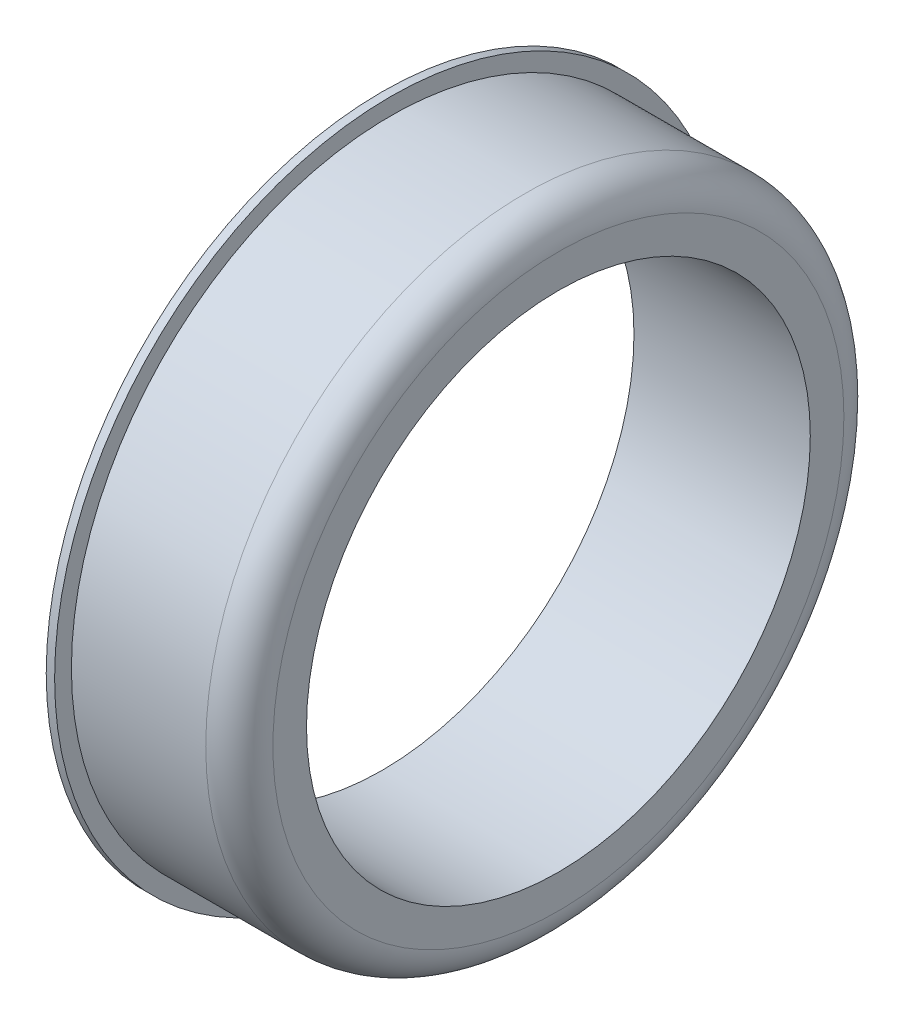
SolidWorks part; units mm, degrees
ref_plane "Front Plane" through (0, 0, 0) normal (0, 0, 1) x (1, 0, 0)
ref_plane "Top Plane" through (0, 0, 0) normal (0, 1, 0) x (1, 0, 0)
ref_plane "Right Plane" through (0, 0, 0) normal (1, 0, 0) x (0, 0, -1)
sketch "Sketch1" plane through (0, 0, 0) normal (1, 0, 0) x (0, 0, -1)
  line L0 (-10, 0) -> (10, 0) construction
  line L1 (0, 10) -> (0, -10) construction
  circle A0 centre (0, 0) radius 10
  circle A1 centre (0, 0) radius 7.5
  dimension "D1" = 20
  dimension "D2" = 15
extrude "Boss-Extrude1" add sketch "Sketch1" along normal blind 0.25
sketch "Sketch2" plane through (0.25, 0, 0) normal (1, 0, 0) x (0, 0, -1)
  circle A0 centre (0, 0) radius 9.5
  circle A1 centre (0, 0) radius 7.5
  dimension "D1" = 19
  dimension "D2" = 15
extrude "Boss-Extrude2" add sketch "Sketch2" along normal blind 5
fillet "Fillet1" radius 1 1 edges at (5.25, 0, -9.5)
